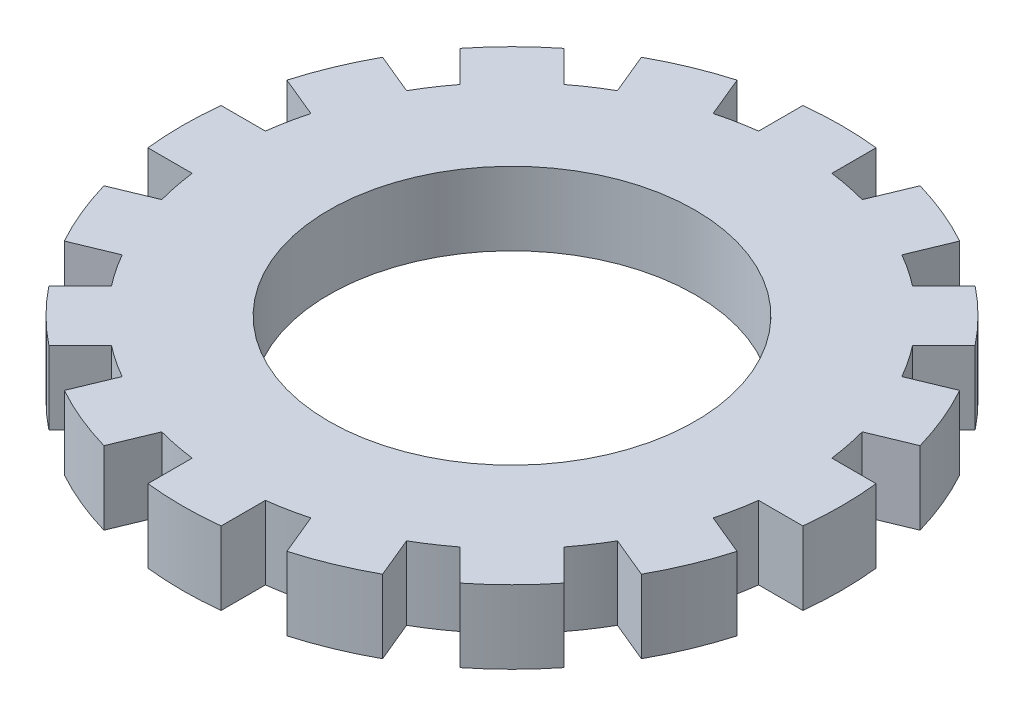
SolidWorks part; units mm, degrees
ref_plane "Front Plane" through (0, 0, 0) normal (0, 0, 1) x (1, 0, 0)
ref_plane "Top Plane" through (0, 0, 0) normal (0, 1, 0) x (1, 0, 0)
ref_plane "Right Plane" through (0, 0, 0) normal (1, 0, 0) x (0, 0, -1)
sketch "Sketch1" plane through (0, 0, 0) normal (0, 1, 0) x (1, 0, 0)
  line L0 (0, 0) -> (0, 52.9211) construction
  line L1 (10.1821, 37.6474) -> (12.4947, 43.2306)
  line L2 (5, 38.6782) -> (5, 44.7214)
  line L3 (-5, 38.6782) -> (-5, 44.7214)
  line L4 (19.4209, 33.8205) -> (21.7335, 39.4037)
  line L5 (23.8141, 30.8851) -> (28.0872, 35.1583)
  line L6 (30.8851, 23.8141) -> (35.1583, 28.0872)
  line L7 (33.8205, 19.4209) -> (39.4037, 21.7335)
  line L8 (37.6474, 10.1821) -> (43.2306, 12.4947)
  line L9 (38.6782, 5) -> (44.7214, 5)
  line L10 (38.6782, -5) -> (44.7214, -5)
  line L11 (37.6474, -10.1821) -> (43.2306, -12.4947)
  line L12 (33.8205, -19.4209) -> (39.4037, -21.7335)
  line L13 (30.8851, -23.8141) -> (35.1583, -28.0872)
  line L14 (23.8141, -30.8851) -> (28.0872, -35.1583)
  line L15 (19.4209, -33.8205) -> (21.7335, -39.4037)
  line L16 (10.1821, -37.6474) -> (12.4947, -43.2306)
  line L17 (5, -38.6782) -> (5, -44.7214)
  line L18 (-5, -38.6782) -> (-5, -44.7214)
  line L19 (-10.1821, -37.6474) -> (-12.4947, -43.2306)
  line L20 (-19.4209, -33.8205) -> (-21.7335, -39.4037)
  line L21 (-23.8141, -30.8851) -> (-28.0872, -35.1583)
  line L22 (-30.8851, -23.8141) -> (-35.1583, -28.0872)
  line L23 (-33.8205, -19.4209) -> (-39.4037, -21.7335)
  line L24 (-37.6474, -10.1821) -> (-43.2306, -12.4947)
  line L25 (-38.6782, -5) -> (-44.7214, -5)
  line L26 (-38.6782, 5) -> (-44.7214, 5)
  line L27 (-37.6474, 10.1821) -> (-43.2306, 12.4947)
  line L28 (-33.8205, 19.4209) -> (-39.4037, 21.7335)
  line L29 (-30.8851, 23.8141) -> (-35.1583, 28.0872)
  line L30 (-23.8141, 30.8851) -> (-28.0872, 35.1583)
  line L31 (-19.4209, 33.8205) -> (-21.7335, 39.4037)
  line L32 (-10.1821, 37.6474) -> (-12.4947, 43.2306)
  arc A0 (-19.4209, 33.8205) -> (-23.8141, 30.8851) centre (0, 0) ccw
  arc A1 (-28.0872, 35.1583) -> (-35.1583, 28.0872) centre (0, 0) ccw
  circle A2 centre (0, 0) radius 25
  arc A3 (-30.8851, 23.8141) -> (-33.8205, 19.4209) centre (0, 0) ccw
  arc A4 (-37.6474, 10.1821) -> (-38.6782, 5) centre (0, 0) ccw
  arc A5 (-38.6782, -5) -> (-37.6474, -10.1821) centre (0, 0) ccw
  arc A6 (-33.8205, -19.4209) -> (-30.8851, -23.8141) centre (0, 0) ccw
  arc A7 (-23.8141, -30.8851) -> (-19.4209, -33.8205) centre (0, 0) ccw
  arc A8 (-10.1821, -37.6474) -> (-5, -38.6782) centre (0, 0) ccw
  arc A9 (5, -38.6782) -> (10.1821, -37.6474) centre (0, 0) ccw
  arc A10 (19.4209, -33.8205) -> (23.8141, -30.8851) centre (0, 0) ccw
  arc A11 (30.8851, -23.8141) -> (33.8205, -19.4209) centre (0, 0) ccw
  arc A12 (37.6474, -10.1821) -> (38.6782, -5) centre (0, 0) ccw
  arc A13 (38.6782, 5) -> (37.6474, 10.1821) centre (0, 0) ccw
  arc A14 (33.8205, 19.4209) -> (30.8851, 23.8141) centre (0, 0) ccw
  arc A15 (23.8141, 30.8851) -> (19.4209, 33.8205) centre (0, 0) ccw
  arc A16 (10.1821, 37.6474) -> (5, 38.6782) centre (0, 0) ccw
  arc A17 (-5, 38.6782) -> (-10.1821, 37.6474) centre (0, 0) ccw
  arc A18 (-12.4947, 43.2306) -> (-21.7335, 39.4037) centre (0, 0) ccw
  arc A19 (5, 44.7214) -> (-5, 44.7214) centre (0, 0) ccw
  arc A20 (21.7335, 39.4037) -> (12.4947, 43.2306) centre (0, 0) ccw
  arc A21 (-39.4037, 21.7335) -> (-43.2306, 12.4947) centre (0, 0) ccw
  arc A22 (-44.7214, 5) -> (-44.7214, -5) centre (0, 0) ccw
  arc A23 (-43.2306, -12.4947) -> (-39.4037, -21.7335) centre (0, 0) ccw
  arc A24 (-35.1583, -28.0872) -> (-28.0872, -35.1583) centre (0, 0) ccw
  arc A25 (-21.7335, -39.4037) -> (-12.4947, -43.2306) centre (0, 0) ccw
  arc A26 (-5, -44.7214) -> (5, -44.7214) centre (0, 0) ccw
  arc A27 (12.4947, -43.2306) -> (21.7335, -39.4037) centre (0, 0) ccw
  arc A28 (28.0872, -35.1583) -> (35.1583, -28.0872) centre (0, 0) ccw
  arc A29 (39.4037, -21.7335) -> (43.2306, -12.4947) centre (0, 0) ccw
  arc A30 (44.7214, -5) -> (44.7214, 5) centre (0, 0) ccw
  arc A31 (43.2306, 12.4947) -> (39.4037, 21.7335) centre (0, 0) ccw
  arc A32 (35.1583, 28.0872) -> (28.0872, 35.1583) centre (0, 0) ccw
  point P8 (0, 0)
  point P12 (0, 0)
  point P13 (0, 0)
  point P73 (0, 0)
  dimension "D1" = 90
  dimension "D2" = 78
  dimension "D3" = 50
  dimension "D5" = 5
  dimension "D6" = 10
  dimension "D4" = 10
  dimension "D7" = 16
extrude "Boss-Extrude1" add sketch "Sketch1" along normal mid plane 10
